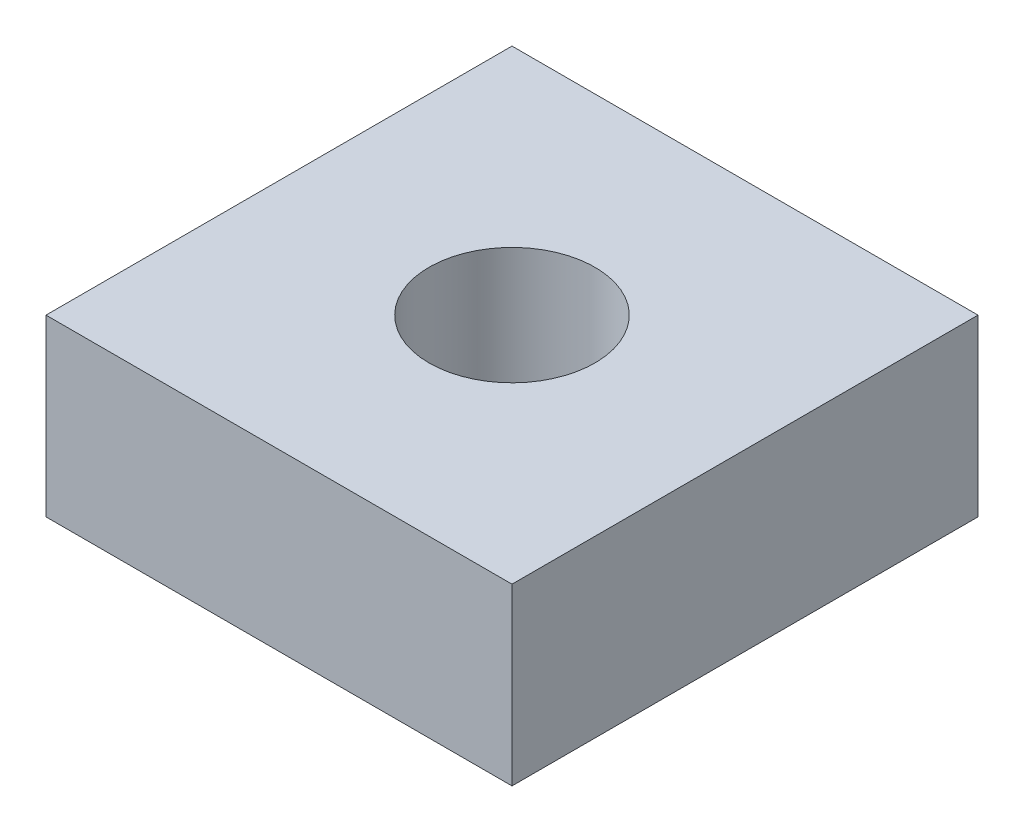
SolidWorks part; units mm, degrees
ref_plane "Front Plane" through (0, 0, 0) normal (0, 0, 1) x (1, 0, 0)
ref_plane "Top Plane" through (0, 0, 0) normal (0, 1, 0) x (1, 0, 0)
ref_plane "Right Plane" through (0, 0, 0) normal (1, 0, 0) x (0, 0, -1)
sketch "Sketch1" plane through (0, 0, 0) normal (0, 1, 0) x (1, 0, 0)
  line L1 (-3.175, -3.175) -> (3.175, -3.175)
  line L2 (-3.175, -3.175) -> (-3.175, 3.175)
  line L3 (-3.175, 3.175) -> (3.175, 3.175)
  line L4 (3.175, -3.175) -> (3.175, 3.175)
  line L5 (-3.175, -3.175) -> (3.175, 3.175) construction
  line L6 (-3.175, 3.175) -> (3.175, -3.175) construction
  point P0 (0, 0)
  dimension "D1" = 6.35
  dimension "D2" = 6.35
extrude "Boss-Extrude1" add sketch "Sketch1" along normal blind 2.3813
hole_wizard "#4-40 Tapped Hole1" positions "Sketch2" profile "Sketch4" tap size "#4-40" standard "ANSI Inch" end condition through all
sketch "Sketch2" plane through (0, 2.3813, 0) normal (0, 1, 0) x (1, 0, 0)
  line L0 (-3.175, 3.175) -> (3.175, -3.175) construction
  point P7 (0, 0)
sketch "Sketch4" plane through (0, 2.3813, 0) normal (1, 0, 0) x (0, 0, 1)
  line L0 (0, 0) -> (0, 2.3813)
  line L1 (0, 2.3813) -> (1.1303, 2.3813)
  line L2 (1.1303, 2.3813) -> (1.1303, 0)
  line L5 (1.1303, 0) -> (0, 0)
  line L11 (0, -6.35) -> (0, 107.95) construction
  dimension "Thru Tap Drill Dia." = 2.2606
  dimension "Thru Tap Drill Depth" = 2.3813
cosmetic thread "Hole Thread1" parameters "D2"=2.8448
